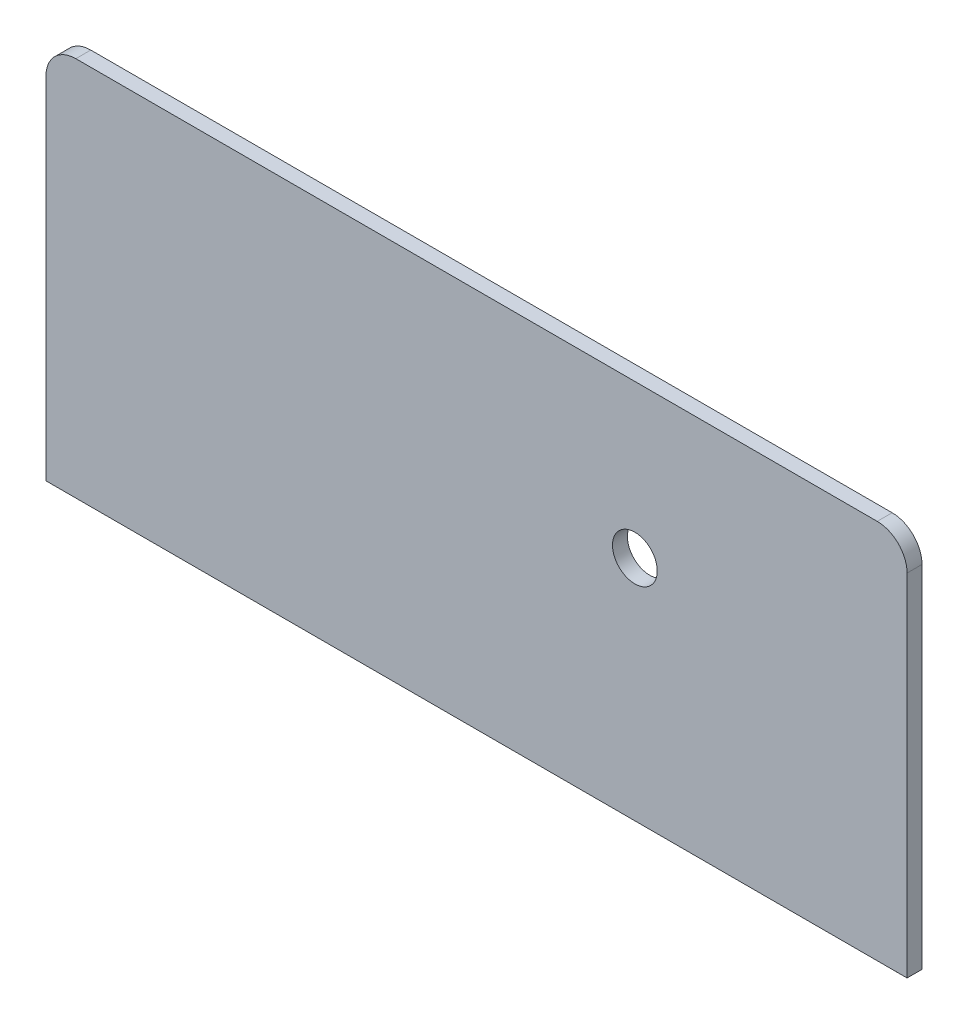
SolidWorks part; units mm, degrees
ref_plane "Front Plane" through (0, 0, 0) normal (0, 0, 1) x (1, 0, 0)
ref_plane "Top Plane" through (0, 0, 0) normal (0, 1, 0) x (1, 0, 0)
ref_plane "Right Plane" through (0, 0, 0) normal (1, 0, 0) x (0, 0, -1)
sketch "Sketch1" plane through (0, 0, 0) normal (0, 0, 1) x (1, 0, 0)
  line L0 (8.1, 39) -> (-49.6, 39)
  line L5 (-47.6, 64.5) -> (6.1, 64.5)
  line L12 (-49.6, 62.5) -> (-49.6, 39)
  line L13 (8.1, 62.5) -> (8.1, 39)
  arc A16 (8.1, 62.5) -> (6.1, 64.5) centre (6.1, 62.5) ccw
  arc A17 (-47.6, 64.5) -> (-49.6, 62.5) centre (-47.6, 62.5) ccw
  circle A20 centre (-10.14, 54.25) radius 1.5
  point P27 (-49.6, 39)
  point P28 (8.1, 39)
  dimension "D8" = 39
  dimension "D9" = 8.1
  dimension "D10" = 18.24
  dimension "D31" = 3
  dimension "D1" = 23.5
  dimension "D2" = 23.5
  dimension "D4" = 53.7
  dimension "D5" = 57.7
  dimension "D6" = 0
  dimension "D7" = 10.25
extrude "Boss-Extrude1" add sketch "Sketch1" along normal blind 1
